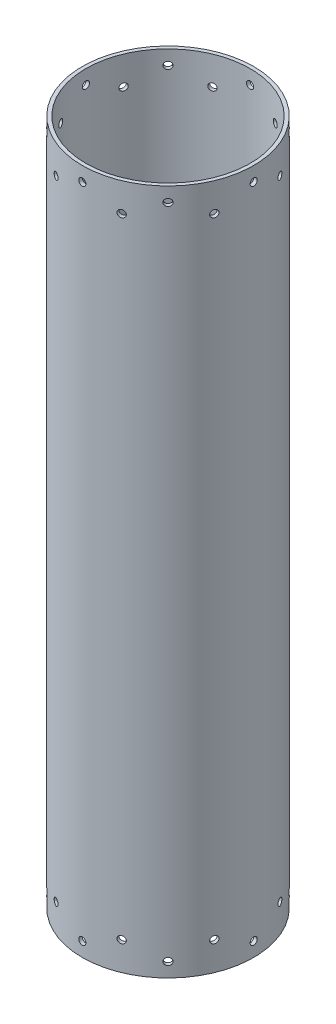
SolidWorks part; units mm, degrees
material "6061-T6 (SS)"
ref_plane "Front Plane" through (0, 0, 0) normal (0, 0, 1) x (1, 0, 0)
ref_plane "Top Plane" through (0, 0, 0) normal (0, 1, 0) x (1, 0, 0)
ref_plane "Right Plane" through (0, 0, 0) normal (1, 0, 0) x (0, 0, -1)
sketch "Sketch2" plane through (0, 0, 0) normal (0, 1, 0) x (1, 0, 0)
  circle A0 centre (0, 0) radius 76.2
  circle A1 centre (0, 0) radius 73.025
  dimension "D1" = 152.4
  dimension "D2" = 3.175
extrude "Boss-Extrude1" add sketch "Sketch2" along normal blind 609.6
sketch "Sketch3" plane through (0, 0, 0) normal (0, 0, 1) x (1, 0, 0)
  line L0 (0, 609.6) -> (0, 596.9) construction
  line L1 (73.025, 609.6) -> (-73.025, 609.6) construction
  circle A0 centre (0, 596.9) radius 3.175
  dimension "D1" = 6.35
  dimension "D2" = 12.7
extrude "Cut-Extrude1" cut sketch "Sketch3" against normal blind 1143
pattern_circular "CirPattern1" count 8 over 360 about axis through (0, 609.6, 0) along (0, -1, 0) of "Cut-Extrude1"
ref_plane "Plane1" through (-29.1605, 0, 70.3996) normal (-0.3827, 0, 0.9239) x (0, -1, 0)
sketch "Sketch6" plane through (-29.1605, 0, 70.3996) normal (-0.3827, 0, 0.9239) x (0, -1, 0)
  line L0 (-609.6, 0) -> (-584.2, 0) construction
  line L1 (-609.6, 76.2) -> (-609.6, -76.2) construction
  circle A0 centre (-584.2, 0) radius 3.175
  dimension "D1" = 6.35
  dimension "D2" = 25.4
extrude "Cut-Extrude2" cut sketch "Sketch6" against normal blind 25.4
pattern_circular "CirPattern2" count 8 over 360 about axis through (0, 609.6, 0) along (0, -1, 0) of "Cut-Extrude2"
ref_plane "Plane2" through (0, 304.8, 0) normal (0, 1, 0) x (1, 0, 0)
mirror "Mirror1" about plane through (0, 304.8, 0) normal (0, 1, 0) of "CirPattern2", "CirPattern1", "Cut-Extrude1", "Cut-Extrude2"
